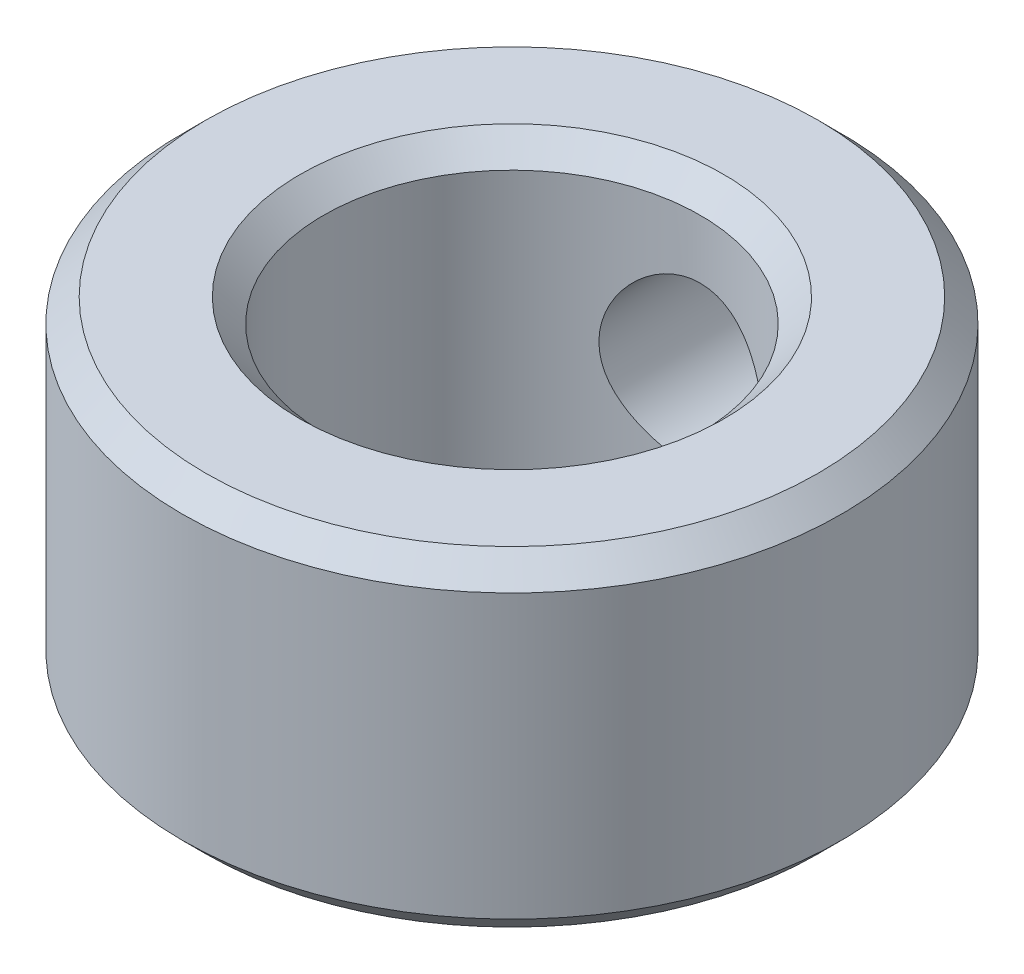
SolidWorks part; units mm, degrees
ref_plane "Front Plane" through (0, 0, 0) normal (0, 0, 1) x (1, 0, 0)
ref_plane "Top Plane" through (0, 0, 0) normal (0, 1, 0) x (1, 0, 0)
ref_plane "Right Plane" through (0, 0, 0) normal (1, 0, 0) x (0, 0, -1)
sketch "Sketch1" plane through (0, 0, 0) normal (0, 1, 0) x (1, 0, 0)
  circle A0 centre (0, 0) radius 4
  circle A1 centre (0, 0) radius 7
  dimension "D1" = 8
  dimension "D2" = 14
extrude "Boss-Extrude1" add sketch "Sketch1" along normal blind 7
sketch "Sketch2" plane through (0, 0, 0) normal (0, 0, 1) x (1, 0, 0)
  line L2 (-7, 0) -> (7, 0) construction
  circle A0 centre (0, 3.5) radius 1.75
  point P2 (0, 0)
  point P5 (0, 0)
  dimension "D2" = 3.5
  dimension "D1" = 3.5
extrude "Cut-Extrude1" cut sketch "Sketch2" against normal up to next
chamfer "Chamfer1" distance 0.5 angle 45 4 edges at (0, 0, 4) (0, 0, 7) (0, 7, 4) (0, 7, 7)
